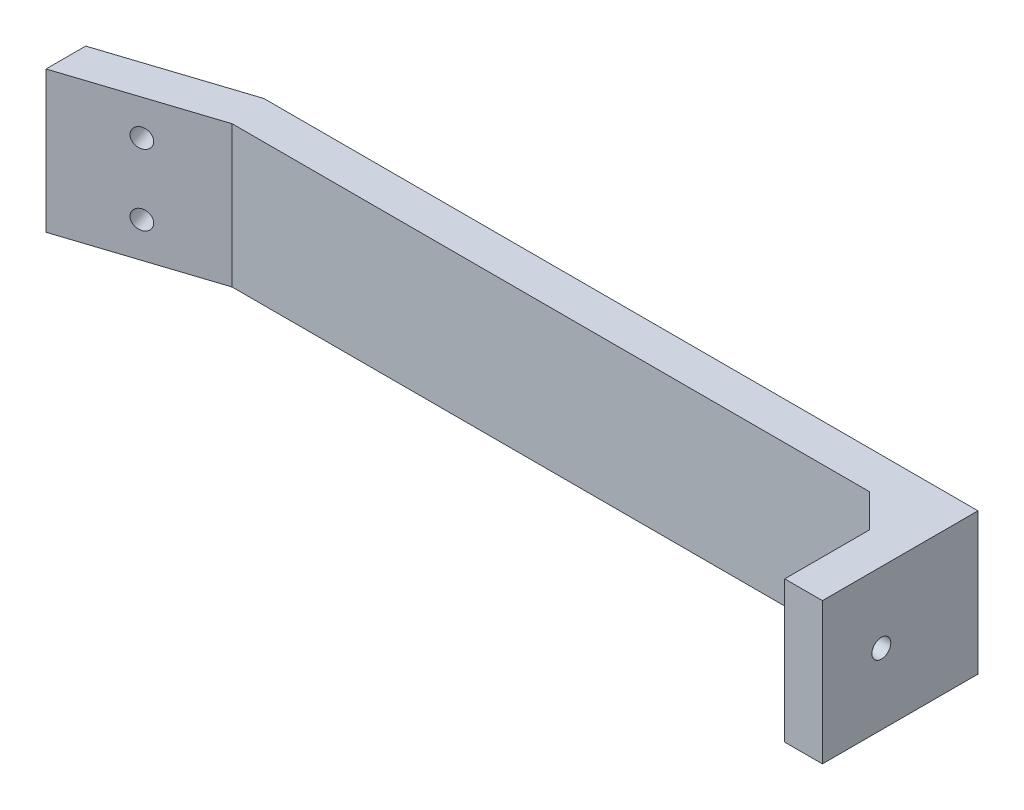
SolidWorks part; units mm, degrees
ref_plane "Front Plane" through (0, 0, 0) normal (0, 0, 1) x (1, 0, 0)
ref_plane "Top Plane" through (0, 0, 0) normal (0, 1, 0) x (1, 0, 0)
ref_plane "Right Plane" through (0, 0, 0) normal (1, 0, 0) x (0, 0, -1)
sketch "Sketch1" plane through (0, 0, 0) normal (0, 0, 1) x (1, 0, 0)
  line L1 (-90, 15) -> (90, 15)
  line L2 (-90, 15) -> (-90, -15)
  line L3 (-90, -15) -> (90, -15)
  line L4 (90, 15) -> (90, -15)
  line L5 (-90, 15) -> (90, -15) construction
  line L6 (-90, -15) -> (90, 15) construction
  point P0 (0, 0)
  dimension "D1" = 180
  dimension "D2" = 30
extrude "Boss-Extrude1" add sketch "Sketch1" along normal blind 50
sketch "Sketch2" plane through (0, -15, 0) normal (0, -1, 0) x (1, 0, 0)
  line L0 (-90, 9.2705) -> (-61.4683, 0)
  line L1 (-90, 50) -> (-90, 0) construction
  line L2 (-90, 0) -> (90, 0) construction
  line L3 (-90, 9.2705) -> (-90, 0)
  line L4 (-90, 0) -> (-61.4683, 0)
  dimension "D1" = 30
  dimension "D2" = 162
extrude "Cut-Extrude1" cut sketch "Sketch2" against normal through all
sketch "Sketch3" plane through (0, -15, 0) normal (0, -1, 0) x (1, 0, 0)
  line L0 (-90, 17.6822) -> (-60.2012, 8)
  line L1 (-90, 50) -> (-90, 9.2705) construction
  line L2 (90, 50) -> (90, 0) construction
  line L3 (90, 8) -> (-60.2012, 8)
  line L4 (-61.4683, 0) -> (-90, 9.2705) construction
  line L5 (-61.4683, 0) -> (90, 0) construction
  line L6 (-90, 17.6822) -> (-90, 50)
  line L7 (-90, 50) -> (90, 50)
  line L8 (90, 50) -> (90, 8)
  dimension "D1" = 8
  dimension "D2" = 8
extrude "Cut-Extrude2" cut sketch "Sketch3" against normal through all
sketch "Sketch4" plane through (0, 0, 8) normal (0, 0, 1) x (1, 0, 0)
  line L0 (-60.2012, -15) -> (90, -15) construction
  line L1 (90, 15) -> (82, 15)
  line L2 (90, 15) -> (90, -15)
  line L3 (90, -15) -> (82, -15)
  line L4 (82, 15) -> (82, -15)
  dimension "D1" = 8
extrude "Boss-Extrude2" add sketch "Sketch4" along normal blind 25
sketch "Sketch5" plane through (82, 0, 0) normal (-1, 0, 0) x (0, 0, 1)
  line L1 (8, -15) -> (15, -15)
  line L2 (8, -15) -> (8, -10)
  line L3 (8, -10) -> (15, -10)
  line L4 (15, -15) -> (15, -10)
  line L5 (8, 15) -> (15, 15)
  line L6 (8, 15) -> (8, 10)
  line L7 (8, 10) -> (15, 10)
  line L8 (15, 15) -> (15, 10)
  dimension "D1" = 7
  dimension "D2" = 7
  dimension "D3" = 5
  dimension "D4" = 5
extrude "Boss-Extrude3" add sketch "Sketch5" along normal blind 7
sketch "Sketch6" plane through (0, -15, 0) normal (0, -1, 0) x (1, 0, 0)
  line L0 (75, 8) -> (82, 15)
  line L1 (82, 15) -> (75, 15)
  line L2 (75, 15) -> (75, 8)
extrude "Cut-Extrude3" cut sketch "Sketch6" against normal through all
sketch "Sketch7" plane through (82, 0, 0) normal (-1, 0, 0) x (0, 0, 1)
  line L0 (33, 15) -> (33, -15) construction
  line L1 (33, 15) -> (15, 15) construction
  circle A0 centre (20.5, 0) radius 2
  dimension "D1" = 4
  dimension "D2" = 12.5
  dimension "D3" = 15
extrude "Cut-Extrude4" cut sketch "Sketch7" against normal blind 15
sketch "Sketch8" plane through (-5.8697, 0, -18.0651) normal (-0.309, 0, -0.9511) x (-0.9511, 0, 0.309)
  line L0 (58.4598, 15) -> (88.4598, 15) construction
  circle A0 centre (74.9244, 7.5) radius 2
  circle A1 centre (74.9244, -7.5) radius 2
  dimension "D1" = 4
  dimension "D2" = 4
  dimension "D3" = 15
  dimension "D4" = 7.5
extrude "Cut-Extrude5" cut sketch "Sketch8" against normal through all
